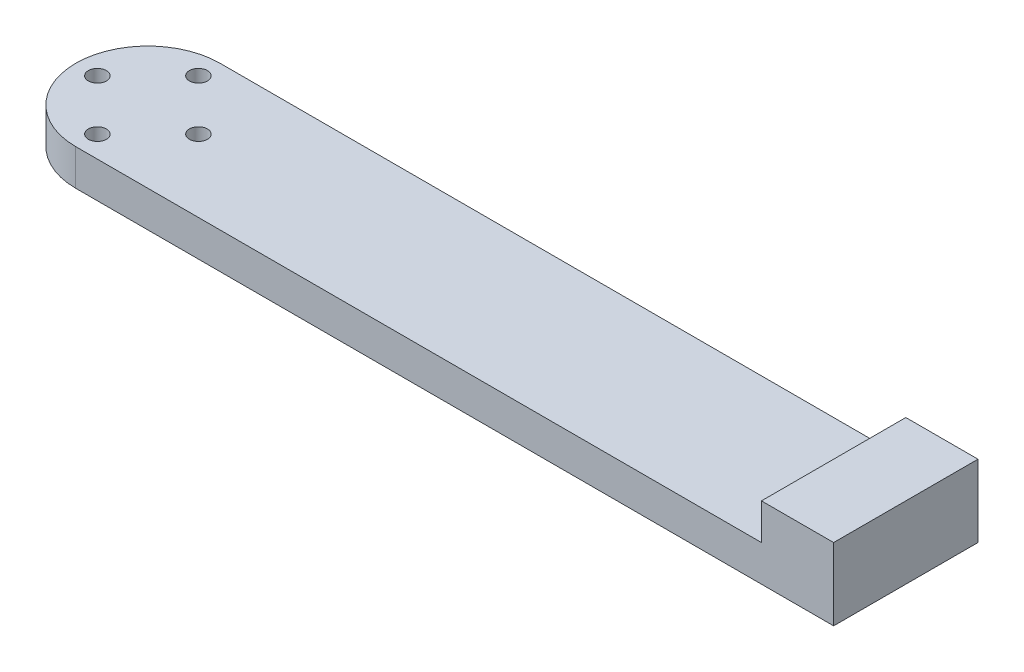
SolidWorks part; units mm, degrees
ref_plane "Front Plane" through (0, 0, 0) normal (0, 0, 1) x (1, 0, 0)
ref_plane "Top Plane" through (0, 0, 0) normal (0, 1, 0) x (1, 0, 0)
ref_plane "Right Plane" through (0, 0, 0) normal (1, 0, 0) x (0, 0, -1)
sketch "Sketch1" plane through (0, 0, 0) normal (0, 1, 0) x (1, 0, 0)
  circle A0 centre (0, 0) radius 10
  circle A1 centre (0, 0) radius 7 construction
  circle A2 centre (0, 7) radius 1.25
  circle A3 centre (7, 0) radius 1.25
  circle A4 centre (0, -7) radius 1.25
  circle A5 centre (-7, 0) radius 1.25
  point P6 (0, 0)
  point P15 (0, 0)
  dimension "D1" = 2.5
  dimension "D2" = 14
  dimension "D3" = 20
  dimension "D4" = 4
extrude "Boss-Extrude1" add sketch "Sketch1" along normal blind 5
sketch "Sketch2" plane through (0, 0, 0) normal (0, 1, 0) x (1, 0, 0)
  line L0 (0, 10) -> (105, 10)
  line L1 (0, -2.75) -> (0, 2.75) construction
  line L2 (105, 10) -> (105, -10)
  line L3 (105, -10) -> (0, -10)
  circle A0 centre (0, 0) radius 10 construction
  arc A1 (0, 10) -> (0, -10) centre (0, 0) cw
  dimension "D1" = 105
extrude "Boss-Extrude2" add sketch "Sketch2" along normal up to surface (5 mm away) up to face at (0, 5, 8.25)
sketch "Sketch3" plane through (0, 0, -10) normal (0, 0, -1) x (-1, 0, 0)
  line L1 (-105, 0) -> (-95, 0)
  line L2 (-105, 0) -> (-105, 10)
  line L3 (-105, 10) -> (-95, 10)
  line L4 (-95, 0) -> (-95, 10)
  dimension "D1" = 10
  dimension "D2" = 10
extrude "Boss-Extrude3" add sketch "Sketch3" against normal up to surface (20 mm away) up to face at (52.5, 2.5, 10)
sketch "Sketch4" plane through (0, 0, -10) normal (0, 0, -1) x (-1, 0, 0)
  line L0 (-105, 0) -> (-95, 10) construction
  line L1 (-105, 10) -> (-95, 0) construction
  line L2 (-95, 5) -> (-95, 10) construction
  line L3 (11, 0) -> (-11, 0) construction
  circle A0 centre (-100, 5) radius 3
  dimension "D1" = 6
extrude "Cut-Extrude1" cut sketch "Sketch4" against normal blind 6
chamfer "Chamfer1" distance 3 angle 45 1 edges at (97, 5, -4)
sketch "Sketch5" plane through (0, 0, -10) normal (0, 0, -1) x (-1, 0, 0)
  line L0 (11, 0) -> (-11, 0) construction
  line L1 (-97, 5) -> (-103, 5)
  line L2 (-97, 5) -> (-97, 0)
  line L3 (-97, 0) -> (-103, 0)
  line L4 (-103, 5) -> (-103, 0)
  circle A0 centre (-100, 5) radius 3 construction
  circle A1 centre (-100, 5) radius 3 construction
extrude "Cut-Extrude2" cut sketch "Sketch5" against normal blind 3
